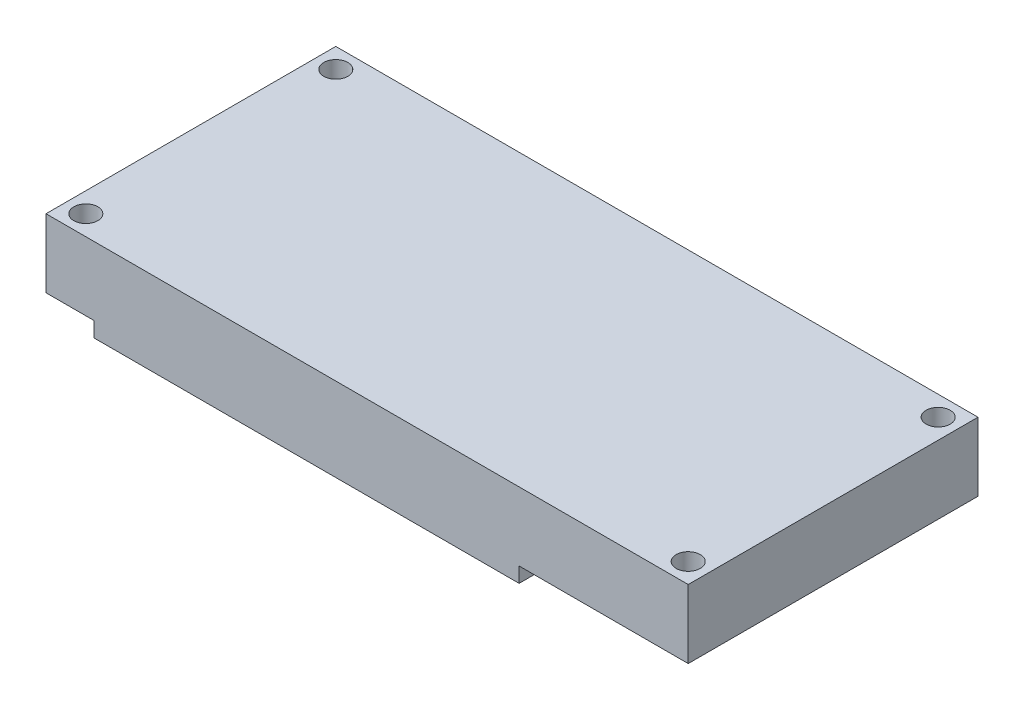
SolidWorks part; units mm, degrees
ref_plane "Front Plane" through (0, 0, 0) normal (0, 0, 1) x (1, 0, 0)
ref_plane "Top Plane" through (0, 0, 0) normal (0, 1, 0) x (1, 0, 0)
ref_plane "Right Plane" through (0, 0, 0) normal (1, 0, 0) x (0, 0, -1)
sketch "Sketch1" plane through (0, 0, 0) normal (0, 1, 0) x (1, 0, 0)
  line L0 (0, 0) -> (0, 12.2612) construction
  line L1 (-39.99, -18.045) -> (39.99, -18.045)
  line L2 (-39.99, -18.045) -> (-39.99, 18.045)
  line L3 (-39.99, 18.045) -> (39.99, 18.045)
  line L4 (39.99, -18.045) -> (39.99, 18.045)
  line L5 (-39.99, -18.045) -> (39.99, 18.045) construction
  line L6 (-39.99, 18.045) -> (39.99, -18.045) construction
  line L8 (10.0745, 0) -> (0, 0) construction
  circle A0 centre (-37.51, 15.565) radius 1.5
  circle A1 centre (37.51, 15.565) radius 1.5
  circle A2 centre (37.51, -15.565) radius 1.5
  circle A3 centre (-37.51, -15.565) radius 1.5
  point P1 (0, 0)
  dimension "D3" = 3
  dimension "D1" = 79.98
  dimension "D2" = 36.09
  dimension "D4" = 2.48
  dimension "D5" = 2.48
extrude "Boss-Extrude1" add sketch "Sketch1" along normal blind 8.53
sketch "Sketch2" plane through (0, 0, 0) normal (0, -1, 0) x (1, 0, 0)
  line L0 (-39.99, 18.045) -> (39.99, 18.045) construction
  line L1 (-33.99, 18.045) -> (18.93, 18.045)
  line L2 (-33.99, 18.045) -> (-33.99, -18.045)
  line L3 (-33.99, -18.045) -> (18.93, -18.045)
  line L4 (18.93, 18.045) -> (18.93, -18.045)
  line L5 (39.99, -18.045) -> (-39.99, -18.045) construction
  line L6 (-39.99, -18.045) -> (-39.99, 18.045) construction
  dimension "D1" = 6
  dimension "D2" = 52.92
extrude "Boss-Extrude2" add sketch "Sketch2" along normal blind 1.88
